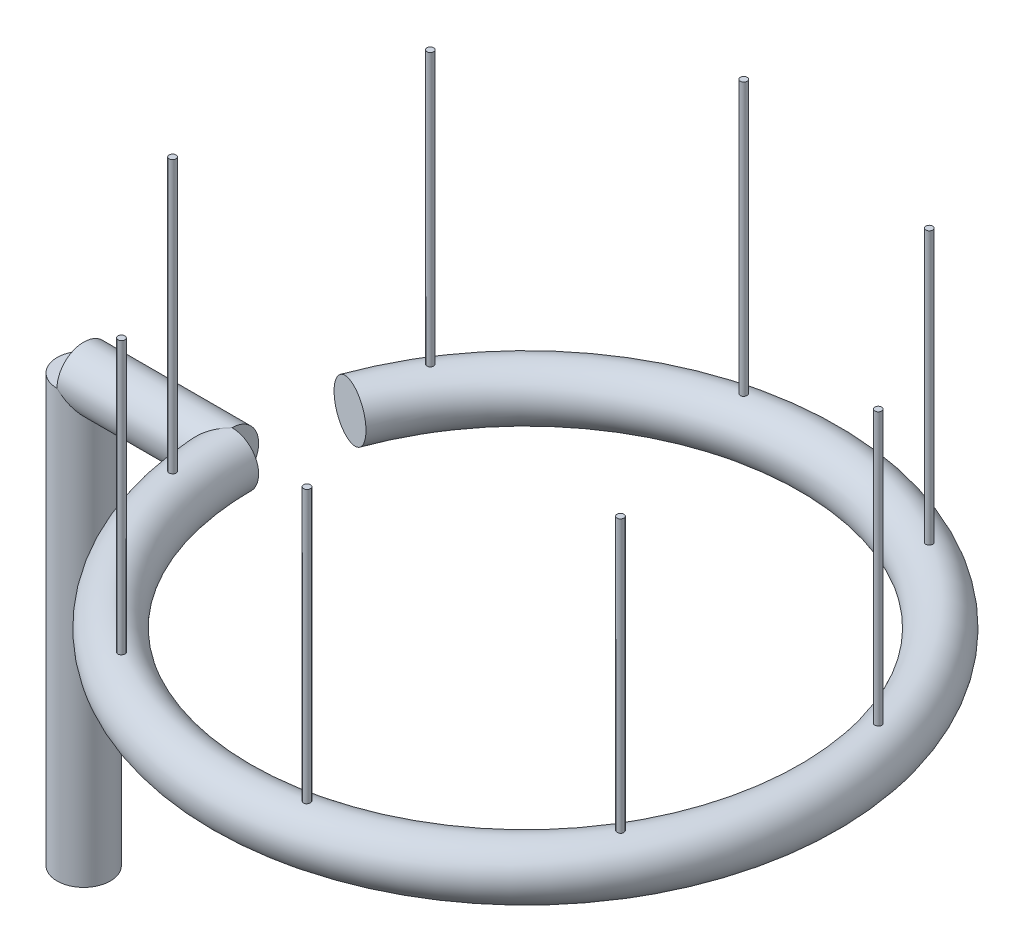
SolidWorks part; units mm, degrees
ref_plane "Front Plane" through (0, 0, 0) normal (0, 0, 1) x (1, 0, 0)
ref_plane "Top Plane" through (0, 0, 0) normal (0, 1, 0) x (1, 0, 0)
ref_plane "Right Plane" through (0, 0, 0) normal (1, 0, 0) x (0, 0, -1)
sketch "Sketch1" plane through (0, 0, 0) normal (0, 0, 1) x (1, 0, 0)
  line L0 (0, 0) -> (0, 18.499) construction
  circle A0 centre (-34.925, 0) radius 3.175
  dimension "D1" = 6.35
  dimension "D2" = 34.925
revolve "Revolve1" add sketch "Sketch1" angle 340 about L0
sketch "Sketch3" plane through (0, 0, 0) normal (0, 0, 1) x (1, 0, 0)
  line L0 (0, 0) -> (0, 35.0105) construction
sketch "Sketch2" plane through (0, 0, 0) normal (0, 1, 0) x (1, 0, 0)
  circle A0 centre (-29.6974, 18.3799) radius 0.4096
  dimension "D2" = 0.8192
  dimension "D1" = 34.925
extrude "Boss-Extrude1" add sketch "Sketch2" along normal blind 35.56
pattern_circular "CirPattern1" count 8 over 360 about axis through (0, 0, 0) along (0, 1, 0) of "Boss-Extrude1"
sketch "Sketch6" plane through (0, 0, 0) normal (0, 0, -1) x (-1, 0, 0)
  line L0 (34.925, 0) -> (42.9594, 0) construction
  line L1 (34.925, 0) -> (34.925, 7.5759) construction
ref_plane "Plane1" through (-34.925, 0, 0) normal (-1, 0, 0) x (0, 1, 0)
sketch "Sketch7" plane through (-34.925, 0, 0) normal (-1, 0, 0) x (0, 1, 0)
  circle A0 centre (0, 0) radius 3.175
extrude "Boss-Extrude2" add sketch "Sketch7" along normal blind 17.653
sketch "Sketch8" plane through (0, 0, 0) normal (0, 0, -1) x (-1, 0, 0)
  line L0 (34.925, 0) -> (34.925, 7.5759) construction
  line L1 (34.925, 3.175) -> (34.925, -3.175)
  arc A0 (34.925, 3.175) -> (34.925, -3.175) centre (34.925, 0) ccw
  arc A1 (34.925, 3.175) -> (34.925, -3.175) centre (34.925, 0) ccw construction
sketch "Sketch9" plane through (-52.578, 0, 0) normal (-1, 0, 0) x (0, 0, 1)
  line L0 (0, 0) -> (-13.2854, 0) construction
  line L2 (0, 3.175) -> (0, -3.175) construction
ref_plane "Plane2" through (0, 0, 0) normal (0, 1, 0) x (0, 0, -1)
sketch "Sketch10" plane through (0, 0, 0) normal (0, 1, 0) x (0, 0, -1)
  line L0 (3.175, 52.578) -> (-3.175, 52.578) construction
  circle A0 centre (0, 52.578) radius 3.175
extrude "Boss-Extrude3" add sketch "Sketch10" against normal blind 50.8
sketch "Sketch12" plane through (0, 0, 0) normal (0, 1, 0) x (1, 0, 0)
  circle A0 centre (0, 0) radius 17.8974 construction
